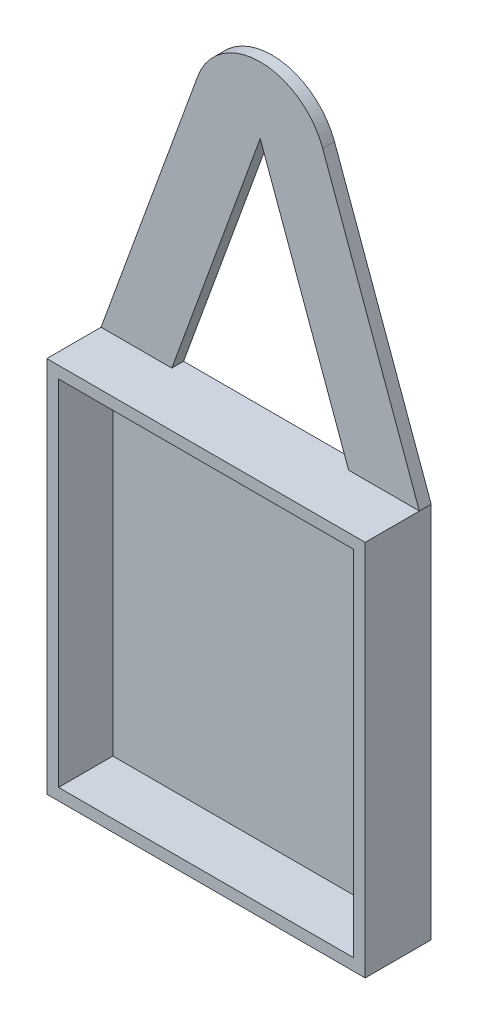
SolidWorks part; units mm, degrees
ref_plane "Front Plane" through (0, 0, 0) normal (0, 0, 1) x (1, 0, 0)
ref_plane "Top Plane" through (0, 0, 0) normal (0, 1, 0) x (1, 0, 0)
ref_plane "Right Plane" through (0, 0, 0) normal (1, 0, 0) x (0, 0, -1)
sketch "Sketch1" plane through (0, 0, 0) normal (0, 0, 1) x (1, 0, 0)
  line L0 (-37.5, 80) -> (37.5, 80)
  line L2 (-67.5, 80) -> (-67.5, -80)
  line L3 (-67.5, -80) -> (67.5, -80)
  line L4 (67.5, 80) -> (67.5, -80)
  line L5 (-67.5, 80) -> (67.5, -80) construction
  line L6 (-67.5, -80) -> (67.5, 80) construction
  line L7 (-37.5, 80) -> (0, 183.0304)
  line L8 (0, 183.0304) -> (37.5, 80)
  line L9 (26.4907, 192.6722) -> (67.5, 80)
  line L11 (-67.5, 80) -> (-26.4907, 192.6722)
  arc A0 (-26.4907, 192.6722) -> (26.4907, 192.6722) centre (0, 183.0304) cw
  point P0 (0, 0)
  dimension "D5" = 70
  dimension "D1" = 135
  dimension "D2" = 160
  dimension "D3" = 30
  dimension "D4" = 30
  dimension "D6" = 70
  dimension "D7" = 70
  dimension "D8" = 70
  dimension "D9" = 160
extrude "Boss-Extrude1" add sketch "Sketch1" along normal blind 5
sketch "Sketch2" plane through (0, 0, 5) normal (0, 0, 1) x (1, 0, 0)
  line L0 (-67.5, 80) -> (67.5, 80)
  line L1 (67.5, 80) -> (67.5, -80)
  line L2 (67.5, -80) -> (-67.5, -80)
  line L3 (-67.5, -80) -> (-67.5, 80)
  line L4 (-37.5, 80) -> (37.5, 80) construction
  line L5 (-62.5, 75) -> (62.5, 75)
  line L6 (-62.5, 75) -> (-62.5, -75)
  line L7 (-62.5, -75) -> (62.5, -75)
  line L8 (62.5, 75) -> (62.5, -75)
  line L9 (-62.5, 75) -> (62.5, -75) construction
  line L10 (-62.5, -75) -> (62.5, 75) construction
  line L13 (67.5, -80) -> (67.5, 80) construction
  line L14 (-67.5, 80) -> (-67.5, -80) construction
  point P4 (0, 0)
  point P14 (0, 0)
  dimension "D1" = 5
  dimension "D2" = 5
  dimension "D3" = 5
  dimension "D4" = 5
extrude "Boss-Extrude2" add sketch "Sketch2" along normal blind 23
